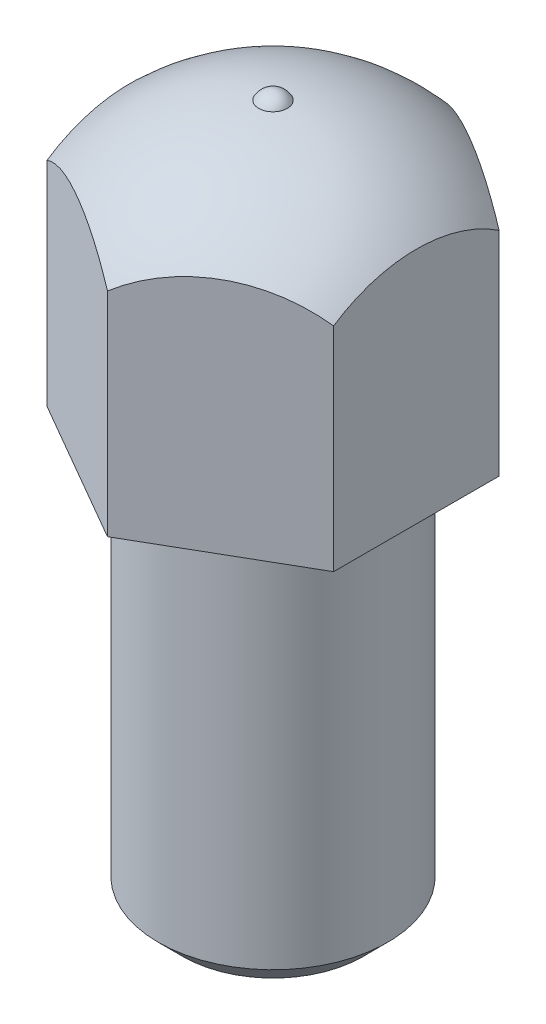
SolidWorks part; units mm, degrees
ref_plane "Спереди" through (0, 0, 0) normal (0, 0, 1) x (1, 0, 0)
ref_plane "Сверху" through (0, 0, 0) normal (0, 1, 0) x (1, 0, 0)
ref_plane "Сбоку" through (0, 0, 0) normal (1, 0, 0) x (0, 0, -1)
ref_plane "Плоскость1" through (0, 0, 0) normal (0, 0, 1) x (1, 0, 0)
sketch "Эскиз1" plane through (0, 0, 0) normal (0, 0, 1) x (1, 0, 0)
  line L0 (3, 3.5506) -> (3, 0)
  line L1 (3, 0) -> (2, 0)
  line L2 (2, 0) -> (2, -6.5705)
  line L3 (2, -6.5705) -> (1.5705, -7)
  line L4 (1.5705, -7) -> (0, -7)
  line L5 (0, -7) -> (0, 5.3)
  line L6 (0, -7) -> (0, 5.3) construction
  arc A0 (0, 5.3) -> (0.25, 5.15) centre (0, 5.0167) cw
  arc A1 (0.25, 5.15) -> (3, 3.5506) centre (0, 1.5562) cw
revolve "Повернуть1" add sketch "Эскиз1" angle 360 about L6
ref_plane "Плоскость2" through (0, 0, 0) normal (0, 1, 0) x (1, 0, 0)
sketch "Эскиз2" plane through (0, 0, 0) normal (0, 1, 0) x (1, 0, 0)
  line L0 (-2.5, 1.4434) -> (-2.5, -1.4434)
  line L1 (-2.5, -1.4434) -> (0, -2.8868)
  line L2 (0, -2.8868) -> (2.5, -1.4434)
  line L3 (2.5, -1.4434) -> (2.5, 1.4434)
  line L4 (2.5, 1.4434) -> (0, 2.8868)
  line L5 (0, 2.8868) -> (-2.5, 1.4434)
  circle A0 centre (0, 0) radius 5
extrude "Вырез-Вытянуть1" cut sketch "Эскиз2" along normal blind 5.3
